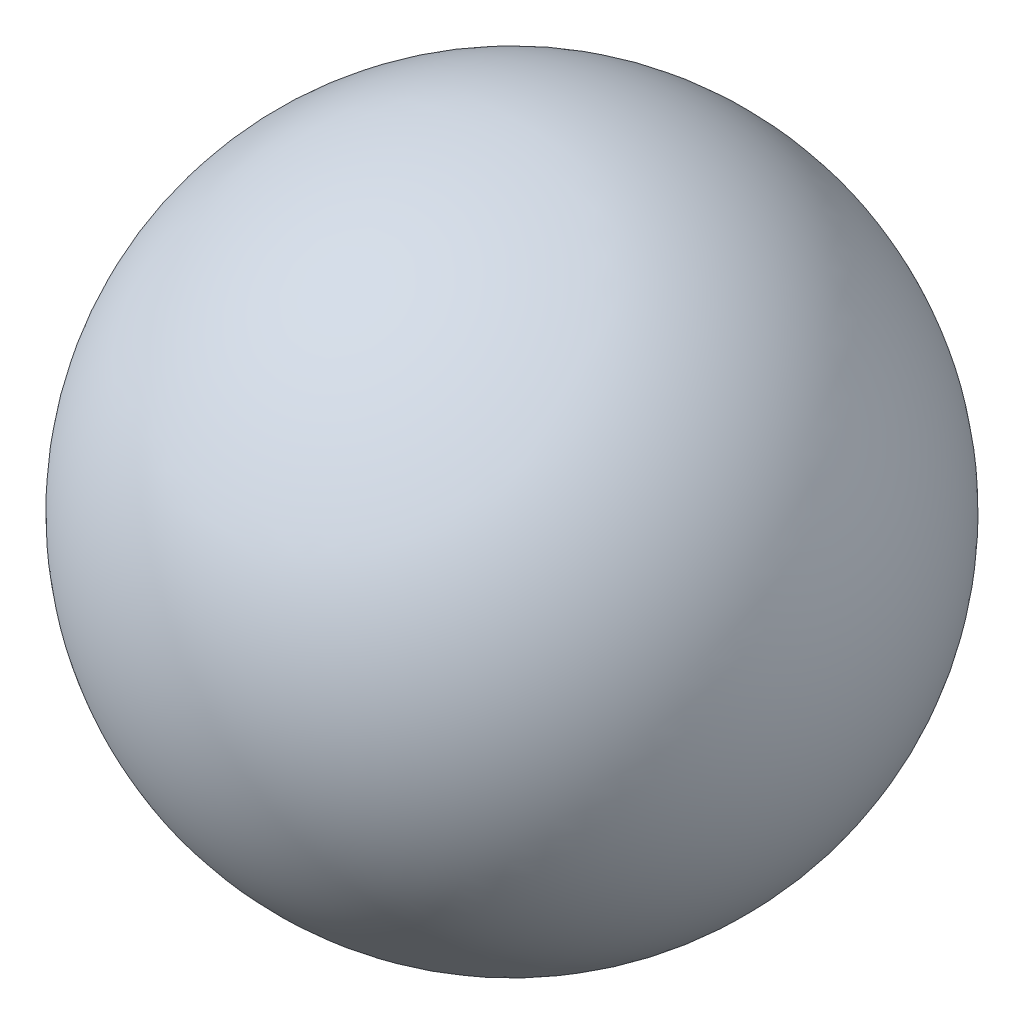
SolidWorks part; units mm, degrees
ref_plane "Front Plane" through (0, 0, 0) normal (0, 0, 1) x (1, 0, 0)
ref_plane "Top Plane" through (0, 0, 0) normal (0, 1, 0) x (1, 0, 0)
ref_plane "Right Plane" through (0, 0, 0) normal (1, 0, 0) x (0, 0, -1)
sketch "Sketch1" plane through (0, 0, 0) normal (0, 1, 0) x (1, 0, 0)
  arc A0 (0, 2.2) -> (0, -2.2) centre (0, 0) ccw
  point P4 (0, 0)
  dimension "D1" = 2.2
sketch "Sketch2" plane through (0, 0, 0) normal (0, 1, 0) x (1, 0, 0)
  line L0 (0, 2.2) -> (0, -2.2) construction
revolve "Revolve-Thin1" add sketch "Sketch1" angle 360 about L0
